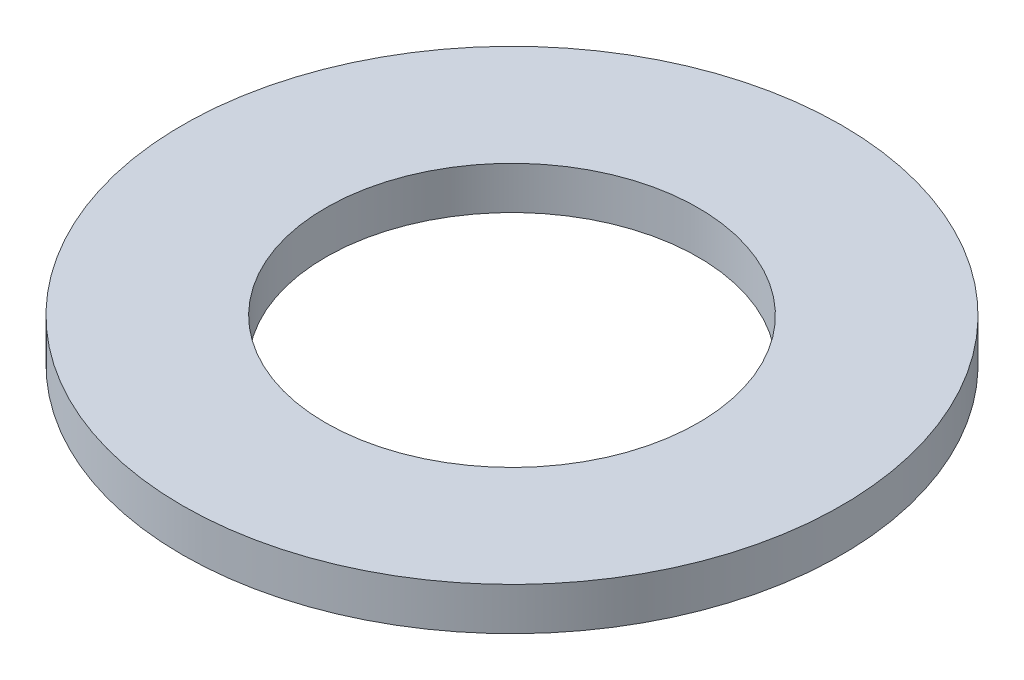
SolidWorks part; units mm, degrees
material "Teak"
ref_plane "Front Plane" through (0, 0, 0) normal (0, 0, 1) x (1, 0, 0)
ref_plane "Top Plane" through (0, 0, 0) normal (0, 1, 0) x (1, 0, 0)
ref_plane "Right Plane" through (0, 0, 0) normal (1, 0, 0) x (0, 0, -1)
sketch "Sketch2" plane through (0, 0, 0) normal (0, 1, 0) x (1, 0, 0)
  circle A0 centre (0, 0) radius 13.1
  circle A1 centre (0, 0) radius 23.1769
  dimension "D1" = 26.2
extrude "Boss-Extrude1" add sketch "Sketch2" along normal blind 3
